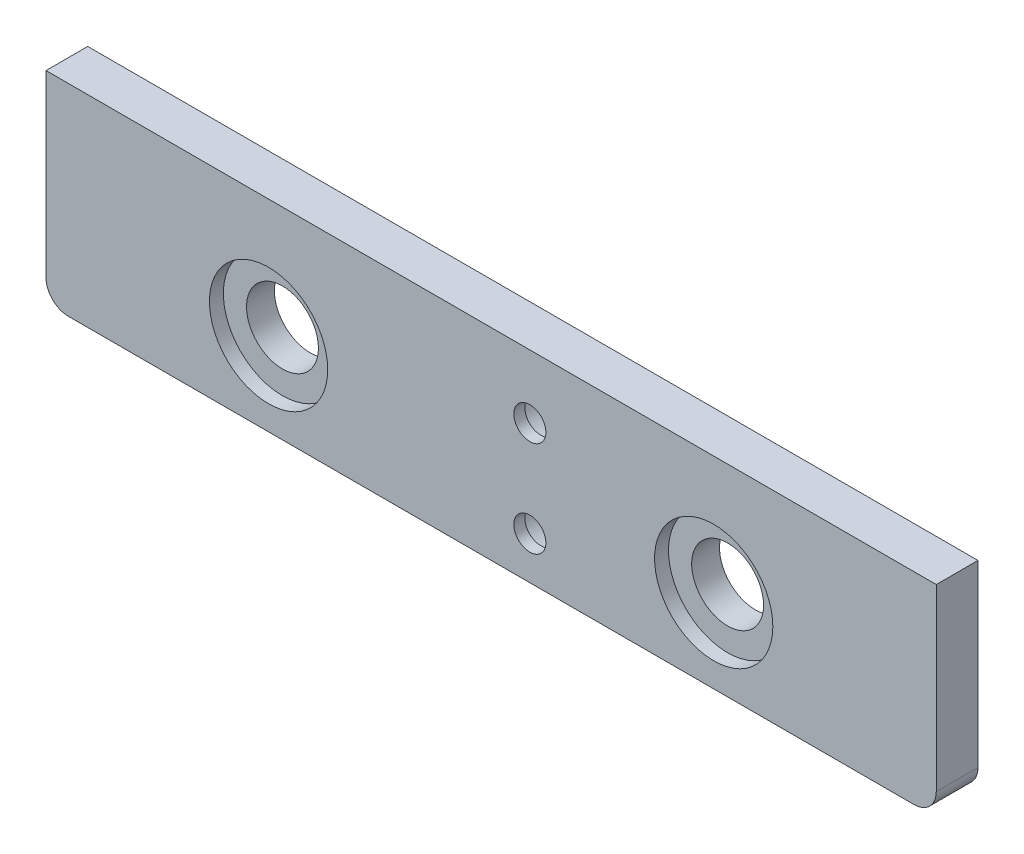
SolidWorks part; units mm, degrees
ref_plane "Front Plane" through (0, 0, 0) normal (0, 0, 1) x (1, 0, 0)
ref_plane "Top Plane" through (0, 0, 0) normal (0, 1, 0) x (1, 0, 0)
ref_plane "Right Plane" through (0, 0, 0) normal (1, 0, 0) x (0, 0, -1)
sketch "Sketch1" plane through (0, 0, 0) normal (0, 0, 1) x (1, 0, 0)
  line L1 (0, 0) -> (101.6, 0)
  line L2 (0, 0) -> (0, 23.0124)
  line L3 (0, 23.0124) -> (101.6, 23.0124)
  line L4 (101.6, 0) -> (101.6, 23.0124)
  dimension "D1" = 23.0124
  dimension "D2" = 101.6
extrude "Boss-Extrude1" add sketch "Sketch1" along normal blind 4.7625
hole_wizard "CBORE for 5/16 Socket Head Cap Screw1" positions "Sketch2" profile "Sketch3" counterbore size "5/16" standard "ANSI Inch" end condition through all
sketch "Sketch2" plane through (0, 0, 4.7625) normal (0, 0, 1) x (1, 0, 0)
  line L1 (0, 9.525) -> (101.6, 9.525) construction
  line L2 (0, 23.0124) -> (0, 0) construction
  line L3 (101.6, 0) -> (101.6, 23.0124) construction
  line L6 (0, 0) -> (101.6, 0) construction
  point P15 (25.4, 9.525)
  point P17 (76.2, 9.525)
  dimension "D1" = 9.525
  dimension "D2" = 25.4
  dimension "D3" = 25.4
sketch "Sketch3" plane through (76.2, 9.525, 4.7625) normal (1, 0, 0) x (0, -1, 0)
  line L0 (0, 0) -> (0, 4.7625)
  line L1 (0, 4.7625) -> (4.1021, 4.7625)
  line L3 (4.1021, 4.7625) -> (4.1021, 1.5875)
  line L4 (4.1021, 1.5875) -> (6.7475, 1.5875)
  line L5 (6.7475, 1.5875) -> (6.7475, 0)
  line L7 (6.7475, 0) -> (0, 0)
  line L11 (0, -6.35) -> (0, 107.95) construction
  dimension "Thru Hole Dia." = 8.2042
  dimension "Thru Hole Depth" = 4.7625
  dimension "C'Bore Dia." = 13.495
  dimension "C'Bore Depth" = 1.5875
hole_wizard "CBORE for #6 Socket Head Cap Screw1" positions "Sketch6" profile "Sketch7" counterbore size "#6" standard "ANSI Inch" end condition through all
sketch "Sketch6" plane through (0, 0, 0) normal (0, 0, -1) x (-1, 0, 0)
  point P0 (-55.2187, 15.7734)
  point P11 (-55.2187, 4.8514)
  point P17 (-55.2187, 15.7734)
  point P19 (-55.2187, 4.8514)
sketch "Sketch7" plane through (55.2187, 15.7734, 0) normal (1, 0, 0) x (0, 1, 0)
  line L0 (0, 0) -> (0, 4.7625)
  line L1 (0, 4.7625) -> (1.8288, 4.7625)
  line L3 (1.8288, 4.7625) -> (1.8288, 3.5052)
  line L4 (1.8288, 3.5052) -> (3.5725, 3.5052)
  line L5 (3.5725, 3.5052) -> (3.5725, 0)
  line L7 (3.5725, 0) -> (0, 0)
  line L11 (0, -6.35) -> (0, 107.95) construction
  dimension "Thru Hole Dia." = 3.6576
  dimension "Thru Hole Depth" = 4.7625
  dimension "C'Bore Dia." = 7.145
  dimension "C'Bore Depth" = 3.5052
fillet "Fillet1" radius 2.54 2 edges at (0, 0, 2.3813) (101.6, 0, 2.3813)
